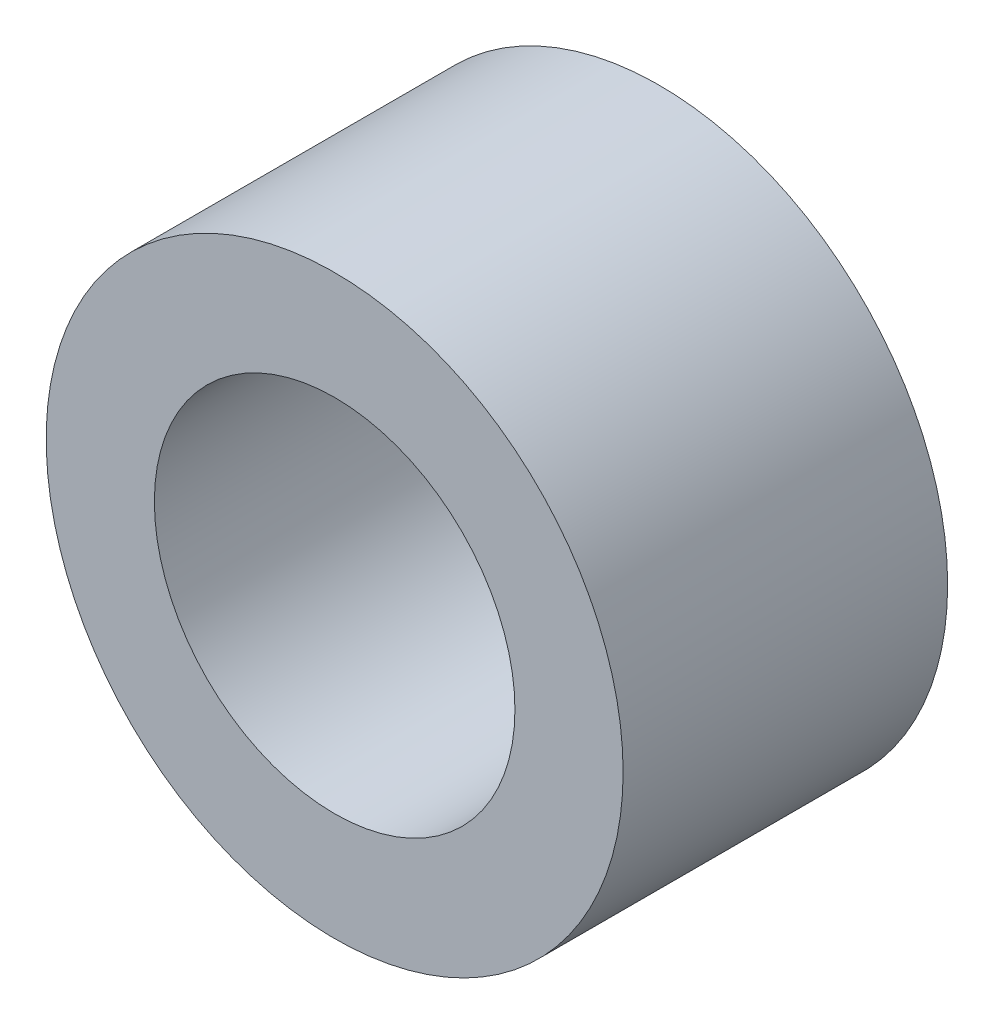
SolidWorks part; units mm, degrees
material "PLA"
ref_plane "前视基准面" through (0, 0, 0) normal (0, 0, 1) x (1, 0, 0)
ref_plane "上视基准面" through (0, 0, 0) normal (0, 1, 0) x (1, 0, 0)
ref_plane "右视基准面" through (0, 0, 0) normal (1, 0, 0) x (0, 0, -1)
sketch "草图1" plane through (0, 0, 0) normal (0, 0, 1) x (1, 0, 0)
  circle A0 centre (0, 0) radius 2.5
  circle A1 centre (0, 0) radius 4
  dimension "D1" = 5
  dimension "D2" = 8
extrude "凸台-拉伸1" add sketch "草图1" along normal blind 4.5
